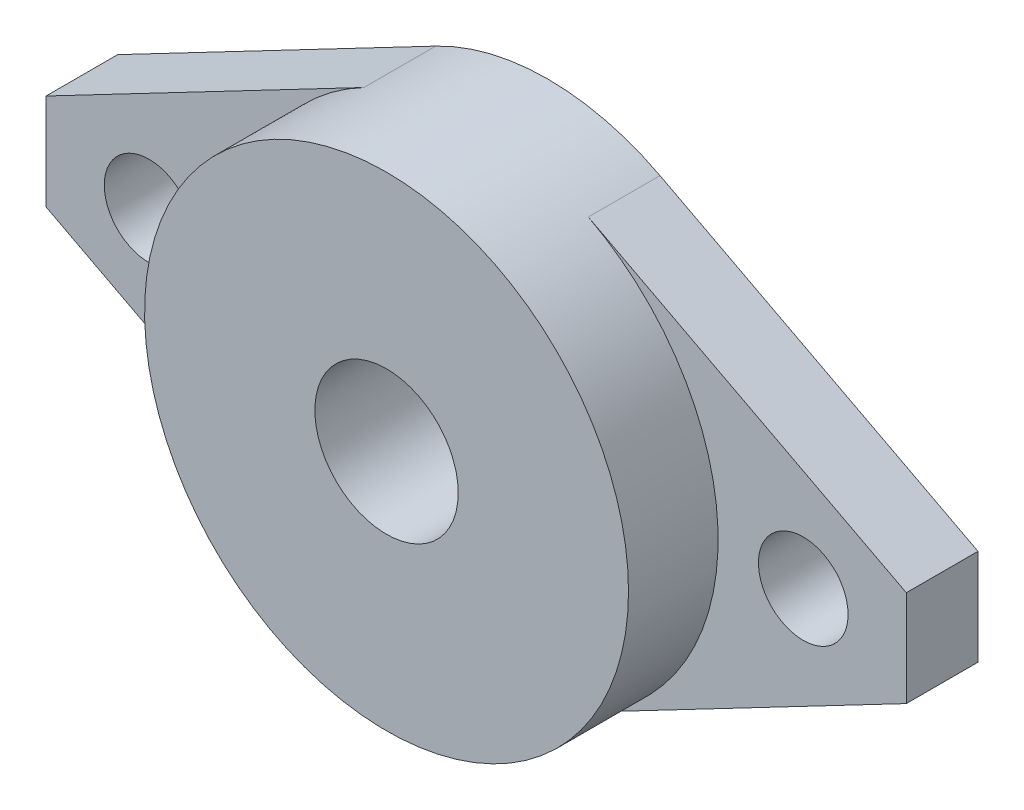
SolidWorks part; units mm, degrees
ref_plane "Alzado" through (0, 0, 0) normal (0, 0, 1) x (1, 0, 0)
ref_plane "Planta" through (0, 0, 0) normal (0, 1, 0) x (1, 0, 0)
ref_plane "Vista lateral" through (0, 0, 0) normal (1, 0, 0) x (0, 0, -1)
sketch "Croquis1" plane through (0, 0, 0) normal (0, 0, 1) x (1, 0, 0)
  line L0 (0, -14.4643) -> (0, 20.4167) construction
  line L1 (24, 2.6786) -> (24, -2.6786)
  line L2 (-24, 2.6786) -> (-24, -2.6786)
  line L3 (-24, 2.6786) -> (-6.2588, 11.9615)
  line L5 (6.2588, 11.9615) -> (24, 2.6786)
  line L6 (24, -2.6786) -> (6.2588, -11.9615)
  line L8 (-6.2588, -11.9615) -> (-24, -2.6786)
  circle A0 centre (18.25, 0) radius 2.5
  circle A1 centre (-18.25, 0) radius 2.5
  arc A2 (-6.2588, -11.9615) -> (6.2588, -11.9615) centre (0, 0) ccw
  circle A3 centre (0, 0) radius 4
  arc A4 (6.2588, 11.9615) -> (-6.2588, 11.9615) centre (0, 0) ccw
  point P12 (24, 0)
  dimension "D1" = 5
  dimension "D3" = 27
  dimension "D4" = 8
  dimension "D2" = 18.25
  dimension "D5" = 24
extrude "Saliente-Extruir1" add sketch "Croquis1" along normal blind 4
sketch "Croquis2" plane through (0, 0, 4) normal (0, 0, 1) x (1, 0, 0)
  circle A0 centre (0, 0) radius 13.5
  circle A1 centre (0, 0) radius 4
  dimension "D1" = 27
extrude "Saliente-Extruir2" add sketch "Croquis2" along normal blind 5
